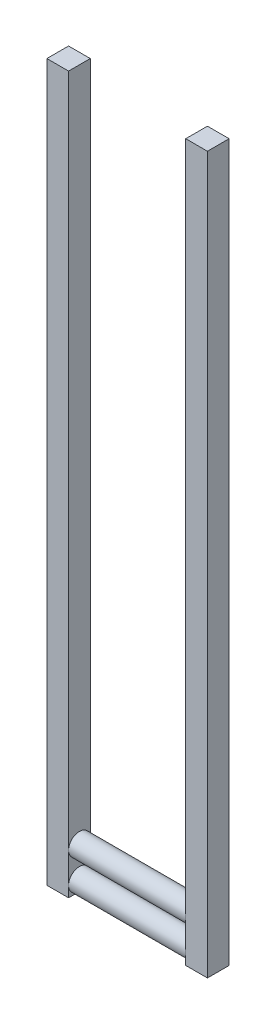
SolidWorks part; units mm, degrees
ref_plane "正面" through (0, 0, 0) normal (0, 0, 1) x (1, 0, 0)
ref_plane "平面" through (0, 0, 0) normal (0, 1, 0) x (1, 0, 0)
ref_plane "右側面" through (0, 0, 0) normal (1, 0, 0) x (0, 0, -1)
sketch "ｽｹｯﾁ1" plane through (0, 0, 0) normal (0, 1, 0) x (1, 0, 0)
  line L1 (-20.5357, 0) -> (-15.5357, 0)
  line L2 (-20.5357, 0) -> (-20.5357, 5)
  line L3 (-20.5357, 5) -> (-15.5357, 5)
  line L4 (-15.5357, 0) -> (-15.5357, 5)
  line L5 (11.4643, 0) -> (16.4643, 0)
  line L6 (11.4643, 0) -> (11.4643, 5)
  line L7 (11.4643, 5) -> (16.4643, 5)
  line L8 (16.4643, 0) -> (16.4643, 5)
  dimension "D1" = 5
  dimension "D2" = 5
  dimension "D3" = 5
  dimension "D4" = 5
  dimension "D5" = 27
extrude "ﾎﾞｽ - 押し出し2" add sketch "ｽｹｯﾁ1" against normal blind 165
sketch "ｽｹｯﾁ2" plane through (-15.5357, 0, 0) normal (1, 0, 0) x (0, 0, -1)
  line L3 (5, -165) -> (5, 0) construction
  line L4 (0, -165) -> (5, -165) construction
  circle A0 centre (2.5, -162.5) radius 2.5
  circle A1 centre (2.5, -155.5) radius 2.5
  dimension "D1" = 5
  dimension "D5" = 5
  dimension "D2" = 2.5
  dimension "D3" = 2.5
  dimension "D4" = 7
  dimension "D6" = 2.5
extrude "ﾎﾞｽ - 押し出し3" add sketch "ｽｹｯﾁ2" along normal blind 27
